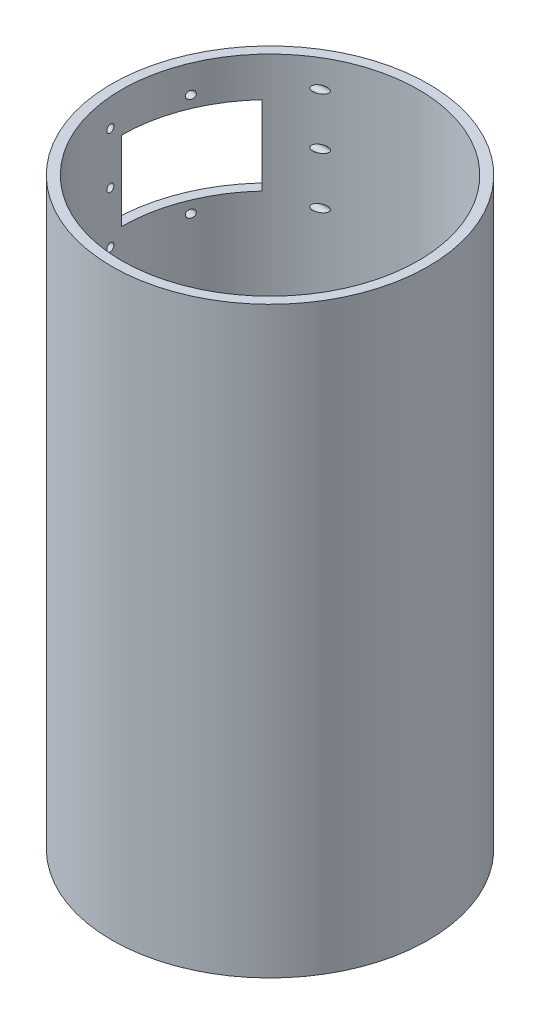
SolidWorks part; units mm, degrees
material "AISI 1045 Steel, cold drawn"
ref_plane "Front Plane" through (0, 0, 0) normal (0, 0, 1) x (1, 0, 0)
ref_plane "Top Plane" through (0, 0, 0) normal (0, 1, 0) x (1, 0, 0)
ref_plane "Right Plane" through (0, 0, 0) normal (1, 0, 0) x (0, 0, -1)
sketch "Sketch2" plane through (0, 0, 0) normal (0, 1, 0) x (1, 0, 0)
  circle A0 centre (0, 0) radius 101.6
  circle A1 centre (0, 0) radius 95.25
  dimension "D1" = 6.35
extrude "Boss-Extrude1" add sketch "Sketch2" along normal blind 374.65
sketch "Sketch3" plane through (0, 0, 0) normal (0, 0, 1) x (1, 0, 0)
  line L2 (0, 0) -> (0, 349.286) construction
  line L3 (0, 349.286) -> (-101.6, 349.286) construction
  line L4 (-101.6, 374.65) -> (-101.6, 0) construction
  line L5 (-101.6, 349.286) -> (-69.85, 349.286) construction
  line L6 (-101.6, 349.286) -> (-69.85, 349.286)
  line L7 (-69.85, 349.286) -> (-69.85, 298.486)
  line L8 (-69.85, 298.486) -> (-101.6, 298.486)
  line L9 (-101.6, 349.286) -> (-101.6, 298.486)
extrude "Cut-Extrude2" cut sketch "Sketch3" against normal through all
sketch "Sketch4" plane through (0, 0, 0) normal (1, 0, 0) x (0, 0, -1)
  line L0 (81.4003, 356.906) -> (81.4003, 290.866)
  line L1 (73.7803, 349.286) -> (0, 349.286)
  line L2 (73.7803, 349.286) -> (73.7803, 298.486)
  line L3 (73.7803, 298.486) -> (0, 298.486)
  line L4 (0, 349.286) -> (0, 298.486)
  line L5 (81.4003, 290.866) -> (-7.62, 290.866)
  line L6 (-7.62, 356.906) -> (-7.62, 290.866)
  line L7 (81.4003, 356.906) -> (-7.62, 356.906)
  line L8 (81.4003, 356.906) -> (36.8902, 356.906)
  line L9 (36.8902, 356.906) -> (-7.62, 356.906)
  circle A0 centre (81.4003, 356.906) radius 2.5
  circle A1 centre (36.8902, 356.906) radius 2.5
  circle A2 centre (-7.62, 356.906) radius 2.5
  circle A3 centre (-7.62, 323.886) radius 2.5
  circle A4 centre (-7.62, 290.866) radius 2.5
  circle A5 centre (36.8902, 290.866) radius 2.5
  circle A6 centre (81.4003, 290.866) radius 2.5
  circle A7 centre (81.4003, 323.886) radius 2.5
  dimension "D1" = 7.62
extrude "Cut-Extrude3" cut sketch "Sketch4" against normal through all contours A0 | A1 | A2 | A3 | A4 | A5 | A6 | A7
